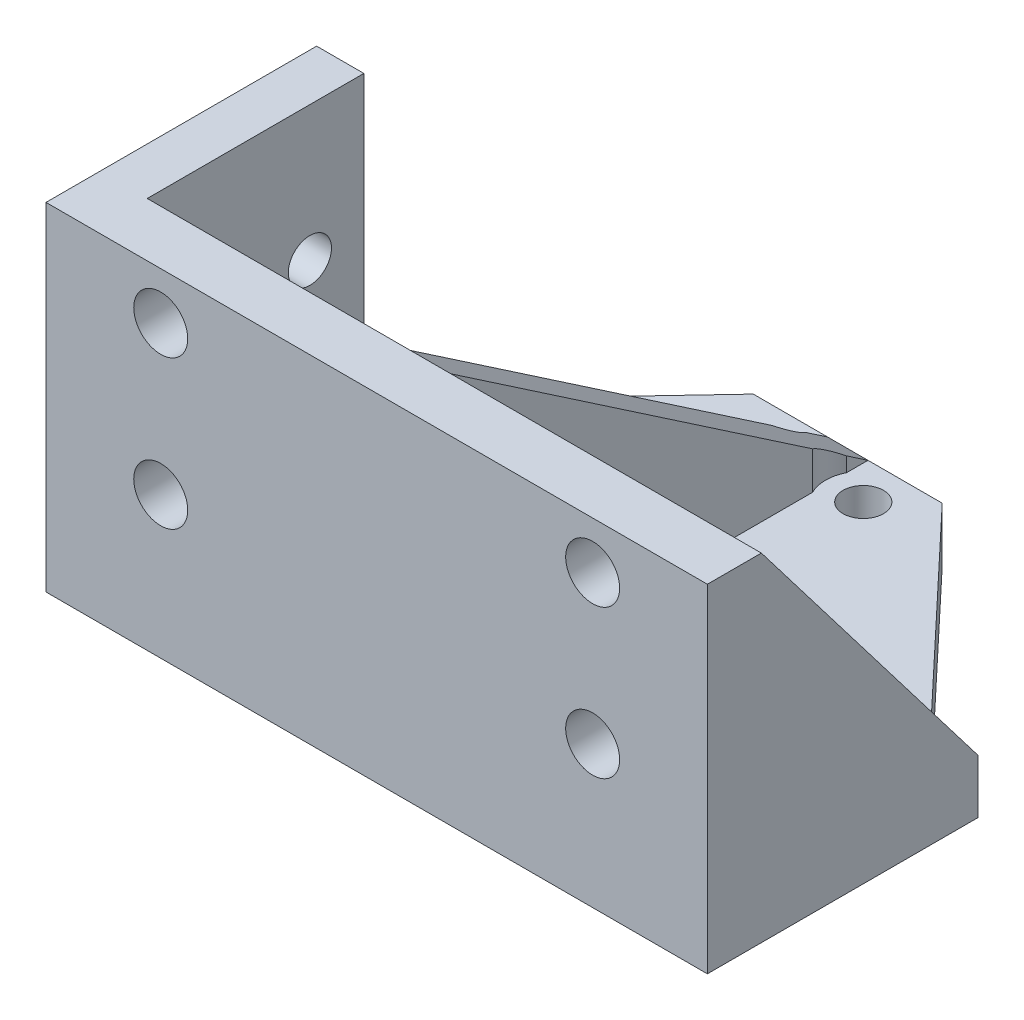
SolidWorks part; units mm, degrees
material "POM 乙缩醛共聚物"
ref_plane "前视基准面" through (0, 0, 0) normal (0, 0, 1) x (1, 0, 0)
ref_plane "上视基准面" through (0, 0, 0) normal (0, 1, 0) x (1, 0, 0)
ref_plane "右视基准面" through (0, 0, 0) normal (1, 0, 0) x (0, 0, -1)
sketch "草图1" plane through (0, 0, 0) normal (1, 0, 0) x (0, 0, -1)
  line L0 (0, 0) -> (0, 25)
  line L2 (34.9, 0) -> (0, 0)
  line L3 (0, 25) -> (4, 25)
  line L5 (4, 25) -> (34.9, 4) construction
  line L6 (34.9, 4) -> (34.9, 0)
  line L7 (34.9, 4) -> (4, 4)
  line L8 (4, 4) -> (4, 25)
  dimension "D1" = 34.9
  dimension "D2" = 25
  dimension "D3" = 4
  dimension "D4" = 4
extrude "凸台-拉伸1" add sketch "草图1" along normal blind 49
sketch "草图3" plane through (0, 4, 0) normal (0, 1, 0) x (1, 0, 0)
  line L0 (49, 0) -> (0, 0) construction
  line L1 (29.5, 4) -> (29.5, 8.55) construction
  line L2 (24.5, 34.9) -> (24.5, 27.1048) construction
  line L3 (49, 34.9) -> (0, 34.9) construction
  line L4 (42.5, 15.55) -> (5.6659, 15.55) construction
  line L5 (31.5, 34.9) -> (45.5, 20.05)
  line L6 (49, 34.9) -> (49, 4) construction
  line L7 (49, 20.05) -> (49, 34.9)
  line L8 (49, 34.9) -> (31.5, 34.9)
  line L9 (0, 20.05) -> (0, 34.9)
  line L10 (17.5, 34.9) -> (3.5, 20.05)
  line L11 (0, 34.9) -> (17.5, 34.9)
  line L12 (49, 20.05) -> (45.5, 20.05)
  line L14 (0, 20.05) -> (3.5, 20.05)
  line L16 (49, 4) -> (0, 4) construction
  circle A0 centre (20.5, 32.05) radius 1.5
  circle A1 centre (28.5, 32.05) radius 1.5
  circle A2 centre (42.5, 15.55) radius 1.5
  circle A3 centre (6.5, 15.55) radius 1.5
  circle A4 centre (29.5, 8.55) radius 1.5
  circle A5 centre (19.5, 8.55) radius 1.5
  dimension "D2" = 3
  dimension "D1" = 32.05
  dimension "D3" = 8
  dimension "D4" = 16.5
  dimension "D5" = 36
  dimension "D6" = 4.5
  dimension "D7" = 7
  dimension "D8" = 3.5
  dimension "D9" = 10
  dimension "D10" = 7
extrude "切除-拉伸1" cut sketch "草图3" against normal through all
sketch "草图5" plane through (49, 0, 0) normal (1, 0, 0) x (0, 0, -1)
  line L0 (20.05, 0) -> (20.05, 4)
  line L1 (20.05, 4) -> (4, 25)
  line L2 (4, 25) -> (0, 25)
  line L3 (0, 25) -> (0, 0)
  line L4 (0, 0) -> (20.05, 0)
extrude "凸台-拉伸3" add sketch "草图5" against normal blind 3.5
sketch "草图6" plane through (0, 0, 0) normal (-1, 0, 0) x (0, 0, 1)
  line L0 (-4, 25) -> (0, 25) construction
  line L1 (0, 25) -> (0, 0) construction
  line L2 (0, 0) -> (-20.05, 0) construction
  line L3 (-20.05, 0) -> (-20.05, 4) construction
  line L4 (-20.05, 4) -> (-4, 25) construction
  line L5 (-4, 25) -> (0, 25)
  line L6 (0, 25) -> (0, 0)
  line L7 (0, 0) -> (-20.05, 0)
  line L8 (-20.05, 0) -> (-20.05, 4)
  line L9 (-20.05, 4) -> (-4, 25)
extrude "凸台-拉伸4" add sketch "草图6" against normal blind 3.5
ref_plane "基准面1" through (24.5, 0, 0) normal (1, 0, 0) x (0, 0, -1)
sketch "草图7" plane through (24.5, 0, 0) normal (1, 0, 0) x (0, 0, -1)
  line L0 (34.9, 4) -> (34.9, 0)
  line L1 (34.9, 0) -> (34.9, 4) construction
  line L2 (34.9, 0) -> (0, 0)
  line L3 (0, 0) -> (0, 25)
  line L4 (0, 25) -> (4, 25)
  line L5 (4, 25) -> (34.9, 4)
extrude "凸台-拉伸5" add sketch "草图7" along normal blind 1.5 and the other way blind 1.5
sketch "草图8" plane through (0, 0, -4) normal (0, 0, -1) x (-1, 0, 0)
  circle A0 centre (-8.5, 10.5) radius 1.65 construction
  circle A1 centre (-8.5, 21.5) radius 1.65 construction
  circle A2 centre (-8.5, 10.5) radius 1.65 construction
  circle A3 centre (-8.5, 21.5) radius 1.65 construction
  circle A4 centre (-40.5, 21.5) radius 1.65 construction
  circle A5 centre (-40.5, 10.5) radius 1.65 construction
  circle A6 centre (-40.5, 21.5) radius 1.65 construction
  circle A7 centre (-40.5, 10.5) radius 1.65 construction
  circle A8 centre (-8.5, 21.5) radius 2
  circle A9 centre (-8.5, 10.5) radius 2
  circle A10 centre (-40.5, 10.5) radius 2
  circle A11 centre (-40.5, 21.5) radius 2
  dimension "D1" = 4
extrude "切除-拉伸2" cut sketch "草图8" against normal blind 10
sketch "草图9" plane through (0, 25, 0) normal (0, 1, 0) x (1, 0, 0)
  line L0 (26, 33.311) -> (26, 30.789)
  line L1 (26, 34.9) -> (26, 4) construction
  line L2 (23, 33.311) -> (23, 30.789)
  line L3 (23, 34.9) -> (23, 4) construction
  arc A0 (26, 33.311) -> (26, 30.789) centre (28.5, 32.05) ccw
  arc A1 (23, 30.789) -> (23, 33.311) centre (20.5, 32.05) ccw
  dimension "D1" = 5.6
extrude "切除-拉伸3" cut sketch "草图9" against normal up to surface (21 mm away) up to face at (42.5, 4, -14.05)
sketch "草图10" plane through (3.5, 0, 0) normal (1, 0, 0) x (0, 0, -1)
  line L0 (20.05, 4) -> (4, 25)
  line L1 (4, 25) -> (20.05, 25)
  line L2 (20.05, 25) -> (20.05, 4)
extrude "凸台-拉伸6" add sketch "草图10" against normal up to surface (3.5 mm away) up to face at (0, 10.8, -8.82)
sketch "草图11" plane through (0, 0, 0) normal (-1, 0, 0) x (0, 0, 1)
  line L0 (-20.05, 25) -> (0, 25) construction
  line L1 (-20.05, 0) -> (-20.05, 25) construction
  circle A0 centre (-8.05, 15) radius 1.6
  circle A1 centre (-16.05, 15) radius 1.6
  dimension "D1" = 3.2
  dimension "D2" = 8
  dimension "D3" = 10
  dimension "D4" = 4
extrude "切除-拉伸4" cut sketch "草图11" against normal blind 10
